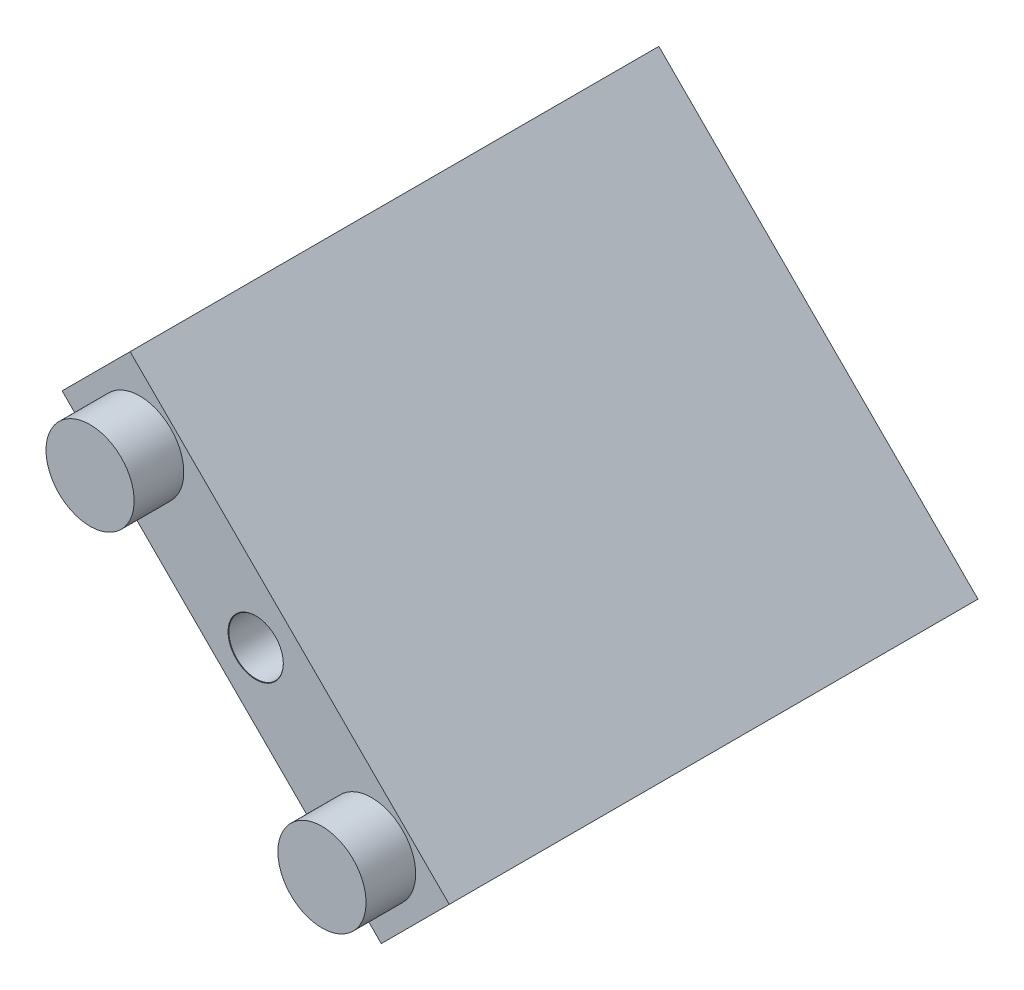
SolidWorks part; units mm, degrees
ref_plane "Front Plane" through (0, 0, 0) normal (0, 0, 1) x (1, 0, 0)
ref_plane "Top Plane" through (0, 0, 0) normal (0, 1, 0) x (1, 0, 0)
ref_plane "Right Plane" through (0, 0, 0) normal (1, 0, 0) x (0, 0, -1)
sketch "Sketch1" plane through (0, 0, 0) normal (0, 0, 1) x (1, 0, 0)
  line L6 (17.1239, -2.983) -> (21.3665, 1.2597)
  line L7 (21.3665, 1.2597) -> (1.4473, 21.1789)
  line L8 (1.4473, 21.1789) -> (-2.7953, 16.9362)
  line L9 (-2.7953, 16.9362) -> (17.1239, -2.983)
  line L10 (0, 0) -> (30.0481, 0) construction
  point P4 (7.1643, 6.9766)
  dimension "D1" = 28.17
  dimension "D2" = 6
  dimension "D3" = 10
  dimension "D4" = 45
  dimension "D5" = 45
  dimension "D6" = 24.1618
extrude "Boss-Extrude1" add sketch "Sketch1" along normal blind 33
sketch "Sketch2" plane through (0, 0, 33) normal (0, 0, 1) x (1, 0, 0)
  line L0 (21.3665, 1.2597) -> (1.4473, 21.1789) construction
  line L1 (1.4473, 21.1789) -> (-2.7953, 16.9362) construction
  line L2 (17.1239, -2.983) -> (21.3665, 1.2597) construction
  circle A0 centre (2.0484, 16.3352) radius 2.75
  circle A1 centre (16.5228, 1.8607) radius 2.75
  dimension "D1" = 5.5
  dimension "D2" = 5.5
  dimension "D3" = 3
  dimension "D4" = 3
  dimension "D6" = 3.85
  dimension "D5" = 3.85
extrude "Boss-Extrude2" add sketch "Sketch2" along normal blind 3.1
hole_wizard "M3 Clearance Hole1" positions "Sketch3" profile "Sketch5" hole size "M3" standard "ANSI Metric"
sketch "Sketch3" plane through (0, 0, 33) normal (0, 0, 1) x (1, 0, 0)
  line L0 (-2.7953, 16.9362) -> (17.1239, -2.983) construction
  line L1 (17.1239, -2.983) -> (21.3665, 1.2597) construction
  point P0 (9.2856, 9.0979)
  dimension "D1" = 3
  dimension "D2" = 14.085
sketch "Sketch5" plane through (9.2856, 9.0979, 33) normal (1, 0, 0) x (0, -1, 0)
  line L0 (0, 0) -> (0, 4.0215)
  line L1 (0, 4.0215) -> (1.7, 3)
  line L2 (1.7, 3) -> (1.7, 0.025)
  line L3 (1.7, 0.025) -> (1.725, 0)
  line L5 (1.725, 0) -> (0, 0)
  line L6 (-1.7, 0.025) -> (-1.725, 0) construction
  line L10 (0, 4.0215) -> (-1.7, 3) construction
  line L11 (0, -6.35) -> (0, 107.95) construction
  dimension "Hole Dia." = 3.4
  dimension "Hole Depth" = 3
  dimension "Near C'Sink Dia." = 3.45
  dimension "Near C'Sink Angle" = 90
  dimension "Drill Angle" = 118
equation "\"D3@Sketch2\"=\"D2@Sketch1\"/2"
equation "\"D4@Sketch2\"=\"D2@Sketch1\"/2"
equation "\"D6@Sketch2\"=1.1+\"D1@Sketch2\"/2"
equation "\"D5@Sketch2\"=1.1+\"D1@Sketch2\"/2"
equation "\"D1@Sketch3\"=\"D2@Sketch1\"/2"
equation "\"D2@Sketch3\"=\"D1@Sketch1\"/2"
